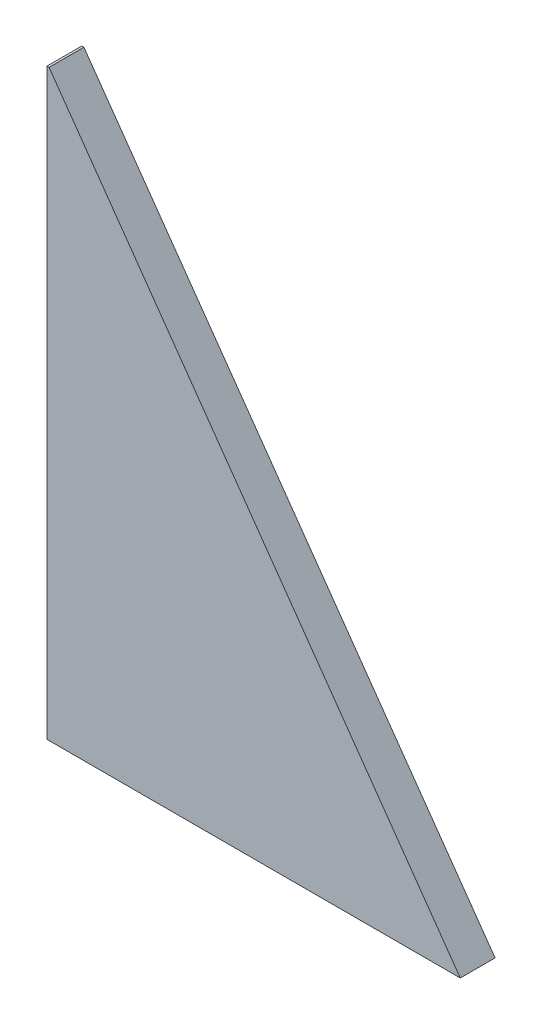
SolidWorks part; units mm, degrees
material "普通碳钢"
ref_plane "前视基准面" through (0, 0, 0) normal (0, 0, 1) x (1, 0, 0)
ref_plane "上视基准面" through (0, 0, 0) normal (0, 1, 0) x (1, 0, 0)
ref_plane "右视基准面" through (0, 0, 0) normal (1, 0, 0) x (0, 0, -1)
sketch "草图1" plane through (0, 0, 0) normal (0, 0, 1) x (1, 0, 0)
  line L8 (0, 0) -> (0, 268)
  line L9 (0, 268) -> (1, 268)
  line L10 (1, 268) -> (190, 0)
  line L11 (190, 0) -> (0, 0)
  dimension "D1" = 190
  dimension "D2" = 268
  dimension "D3" = 1
extrude "凸台-拉伸1" add sketch "草图1" along normal blind 16
